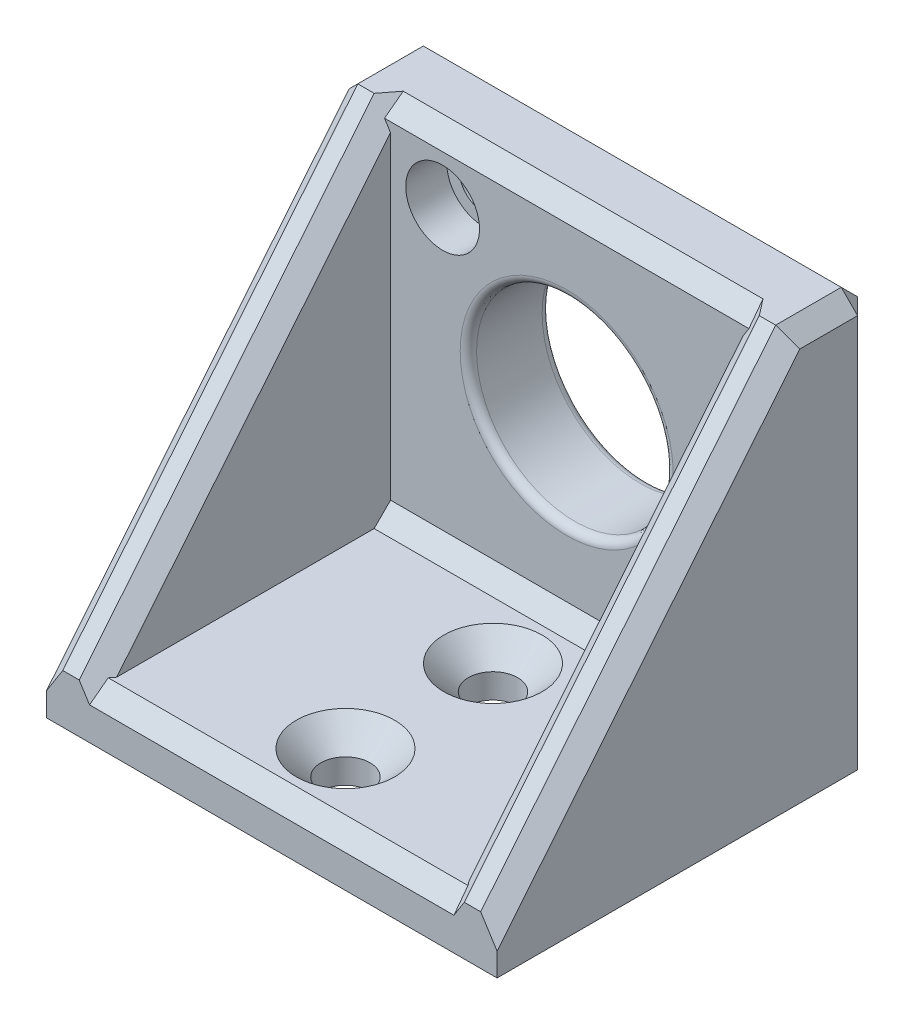
SolidWorks part; units mm, degrees
ref_plane "Plano frontal" through (0, 0, 0) normal (0, 0, 1) x (1, 0, 0)
ref_plane "Plano superior" through (0, 0, 0) normal (0, 1, 0) x (1, 0, 0)
ref_plane "Plano direito" through (0, 0, 0) normal (1, 0, 0) x (0, 0, -1)
sketch "Esboço1" plane through (0, 0, 0) normal (0, 0, 1) x (1, 0, 0)
  line L1 (13.75, 12.5) -> (-13.75, 12.5)
  line L2 (13.75, 12.5) -> (13.75, -12.5)
  line L3 (13.75, -12.5) -> (-13.75, -12.5)
  line L4 (-13.75, 12.5) -> (-13.75, -12.5)
  line L5 (13.75, 12.5) -> (-13.75, -12.5) construction
  line L6 (13.75, -12.5) -> (-13.75, 12.5) construction
  circle A0 centre (0, 0) radius 5.75 construction
  circle A1 centre (0, 0) radius 8.75 construction
  circle A2 centre (0, 0) radius 13.75 construction
  dimension "D1" = 11.5
  dimension "D2" = 3
  dimension "D3" = 5
  dimension "D4" = 25
  dimension "D5" = 27.5
extrude "Ressalto-extrusão1" add sketch "Esboço1" along normal blind 5
sketch "Esboço2" plane through (0, 0, 5) normal (0, 0, 1) x (1, 0, 0)
  line L0 (13.75, -12.5) -> (13.75, 12.5) construction
  line L1 (-13.75, -12.5) -> (13.75, -12.5)
  line L2 (-13.75, -12.5) -> (-13.75, -9.5)
  line L3 (-13.75, -9.5) -> (13.75, -9.5)
  line L4 (13.75, -12.5) -> (13.75, -9.5)
  dimension "D1" = 3
extrude "Ressalto-extrusão2" add sketch "Esboço2" along normal blind 18
sketch "Esboço3" plane through (13.75, 0, 0) normal (1, 0, 0) x (0, 0, -1)
  line L0 (-5, 12.5) -> (-23, -9.5)
  line L1 (-23, -9.5) -> (-5, -9.5)
  line L2 (-5, -9.5) -> (-5, 12.5)
extrude "Ressalto-extrusão3" add sketch "Esboço3" against normal blind 3
sketch "Esboço4" plane through (-13.75, 0, 0) normal (-1, 0, 0) x (0, 0, 1)
  line L3 (5, 12.5) -> (5, -9.5)
  line L4 (5, -9.5) -> (23, -9.5)
  line L5 (23, -9.5) -> (5, 12.5)
  line L6 (5, 12.5) -> (5, -9.5)
  line L7 (5, -9.5) -> (23, -9.5)
  line L8 (23, -9.5) -> (5, 12.5)
  dimension "D1" = 0
extrude "Ressalto-extrusão4" add sketch "Esboço4" against normal blind 3
sketch "Esboço5" plane through (0, -9.5, 0) normal (0, 1, 0) x (1, 0, 0)
  line L0 (0, -14) -> (0, -5) construction
  line L4 (-10.75, -5) -> (-10.75, -23)
  line L5 (-10.75, -23) -> (10.75, -23)
  line L6 (10.75, -23) -> (10.75, -5)
  line L7 (10.75, -5) -> (-10.75, -5)
  line L8 (-10.75, -5) -> (-10.75, -23) construction
  line L9 (-10.75, -23) -> (10.75, -23) construction
  line L10 (10.75, -23) -> (10.75, -5) construction
  line L11 (10.75, -5) -> (-10.75, -5) construction
  line L14 (0, -14) -> (0, -23) construction
  circle A0 centre (0, -9.5) radius 1.5
  circle A1 centre (0, -18.5) radius 1.5
  dimension "D2" = 3
  dimension "D3" = 3
  dimension "D4" = 9
  dimension "D1" = 0
extrude "Corte-extrusão1" cut sketch "Esboço5" against normal blind 5
chamfer "Chanfro1" distance 1.5 angle 45 2 edges at (0, -9.5, 20) (0, -9.5, 11)
chamfer "Chanfro2" distance 1 angle 45 7 edges at (-13.75, 1.5, 14) (13.75, 1.5, 14) (-13.75, 12.5, 2.5) (13.75, 12.5, 2.5) (-13.75, 0, 0) (13.75, 0, 0) (0, 12.5, 0)
chamfer "Chanfro4" distance 1 angle 45 2 edges at (10.75, 1.5, 14) (-10.75, 1.5, 14)
chamfer "Chanfro5" distance 1 angle 45 3 edges at (0, 12.5, 5) (0, -9.5, 5) (0, -9.5, 23)
sketch "Esboço6" plane through (0, 0, 5) normal (0, 0, 1) x (1, 0, 0)
  line L0 (-10.75, -8.5) -> (10.75, 11.5) construction
  line L1 (11.1168, 11.5) -> (-11.1168, 11.5) construction
  line L3 (-4.3931, 5.5866) -> (-10.7499, 11.5) construction
  circle A0 centre (0, 1.5) radius 6
  circle A3 centre (-7.5715, 8.5433) radius 1.5
  dimension "D1" = 12
  dimension "D2" = 3
extrude "Corte-extrusão2" cut sketch "Esboço6" against normal blind 5
fillet "Filete1" radius 0.5 2 edges at (6, 1.5, 5) (6, 1.5, 0)
sketch "Esboço8" plane through (0, 0, 5) normal (0, 0, 1) x (1, 0, 0)
  circle A0 centre (-7.5715, 8.5433) radius 2.25
  dimension "D1" = 4.5
extrude "Corte-extrusão3" cut sketch "Esboço8" against normal blind 2.5
